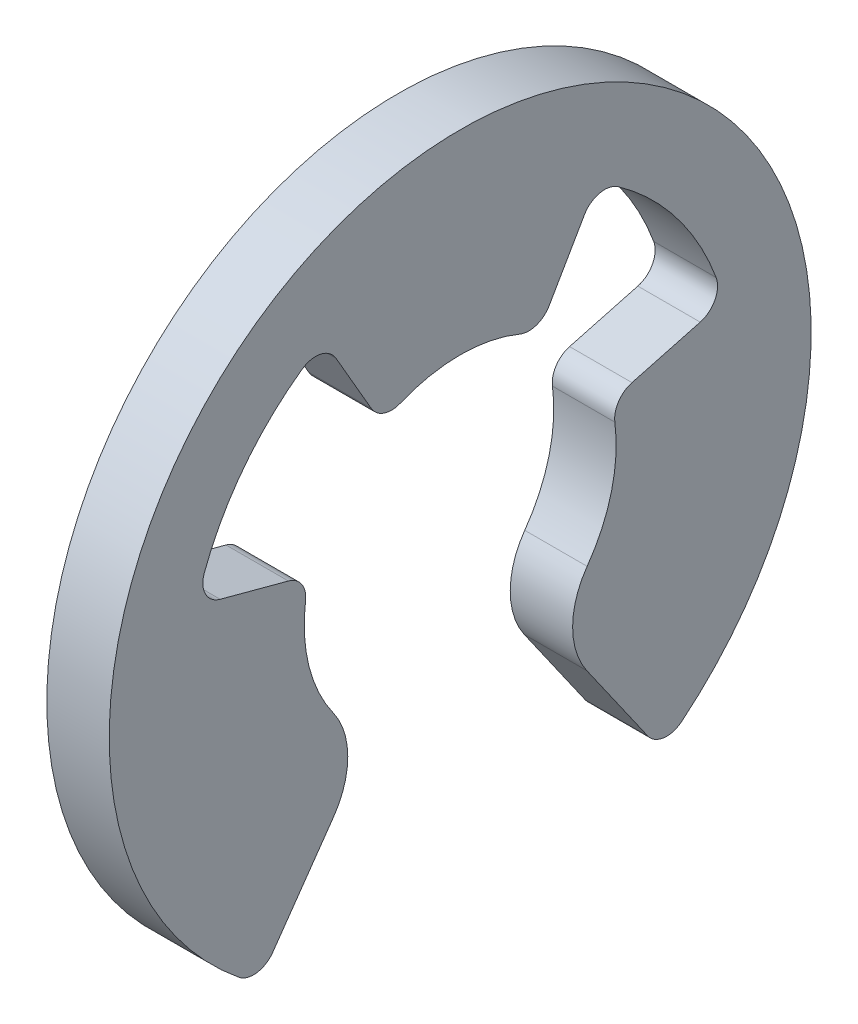
SolidWorks part; units mm, degrees
material "普通碳钢"
ref_plane "前视基准面" through (0, 0, 0) normal (0, 0, 1) x (1, 0, 0)
ref_plane "上视基准面" through (0, 0, 0) normal (0, 1, 0) x (1, 0, 0)
ref_plane "右视基准面" through (0, 0, 0) normal (1, 0, 0) x (0, 0, -1)
sketch "草图1" plane through (0, 0, 0) normal (1, 0, 0) x (0, 0, -1)
  line L0 (0, 0) -> (0, 4.8592) construction
  line L1 (-1.6223, -2.3169) -> (-2.4029, -3.4317)
  line L2 (1.6223, -2.3169) -> (2.4029, -3.4317)
  line L3 (-1.1402, 1.9748) -> (-1.593, 2.7591)
  line L4 (-2.2026, 0.5902) -> (-3.0773, 0.8246)
  line L5 (1.1402, 1.9748) -> (1.593, 2.7591)
  line L6 (2.2026, 0.5902) -> (3.0773, 0.8246)
  arc A0 (1.6276, -1.1622) -> (1.9829, 0.2612) centre (0, 0) ccw
  arc A1 (2.8378, -3.4924) -> (-2.8378, -3.4924) centre (0, 0) ccw
  arc A2 (3.2809, 1.2188) -> (2.0265, 2.8537) centre (0, 0) ccw
  arc A3 (-1.9829, 0.2612) -> (-1.6276, -1.1622) centre (0, 0) ccw
  arc A4 (-2.0265, 2.8537) -> (-3.2809, 1.2188) centre (0, 0) ccw
  arc A5 (0.7655, 1.8477) -> (-0.7655, 1.8477) centre (0, 0) ccw
  arc A6 (1.6276, -1.1622) -> (1.6223, -2.3169) centre (2.4415, -1.7433) ccw
  arc A7 (-1.6223, -2.3169) -> (-1.6276, -1.1622) centre (-2.4415, -1.7433) ccw
  arc A8 (2.8378, -3.4924) -> (2.4029, -3.4317) centre (2.6486, -3.2596) cw
  arc A9 (-2.8378, -3.4924) -> (-2.4029, -3.4317) centre (-2.6486, -3.2596) ccw
  arc A10 (1.9829, 0.2612) -> (2.2026, 0.5902) centre (2.2803, 0.3004) cw
  arc A11 (3.2809, 1.2188) -> (3.0773, 0.8246) centre (2.9997, 1.1144) cw
  arc A12 (2.0265, 2.8537) -> (1.593, 2.7591) centre (1.8528, 2.6091) ccw
  arc A13 (0.7655, 1.8477) -> (1.1402, 1.9748) centre (0.8804, 2.1248) ccw
  arc A14 (-1.1402, 1.9748) -> (-0.7655, 1.8477) centre (-0.8804, 2.1248) ccw
  arc A15 (-2.0265, 2.8537) -> (-1.593, 2.7591) centre (-1.8528, 2.6091) cw
  arc A16 (-3.0773, 0.8246) -> (-3.2809, 1.2188) centre (-2.9997, 1.1144) cw
  arc A17 (-1.9829, 0.2612) -> (-2.2026, 0.5902) centre (-2.2803, 0.3004) ccw
  dimension "D1" = 4
  dimension "D2" = 9
  dimension "D4" = 7
  dimension "D7" = 1
  dimension "D8" = 0.3
  dimension "D3" = 145
  dimension "D5" = 30
  dimension "D6" = 75
extrude "凸台-拉伸1" add sketch "草图1" along normal blind 0.8
